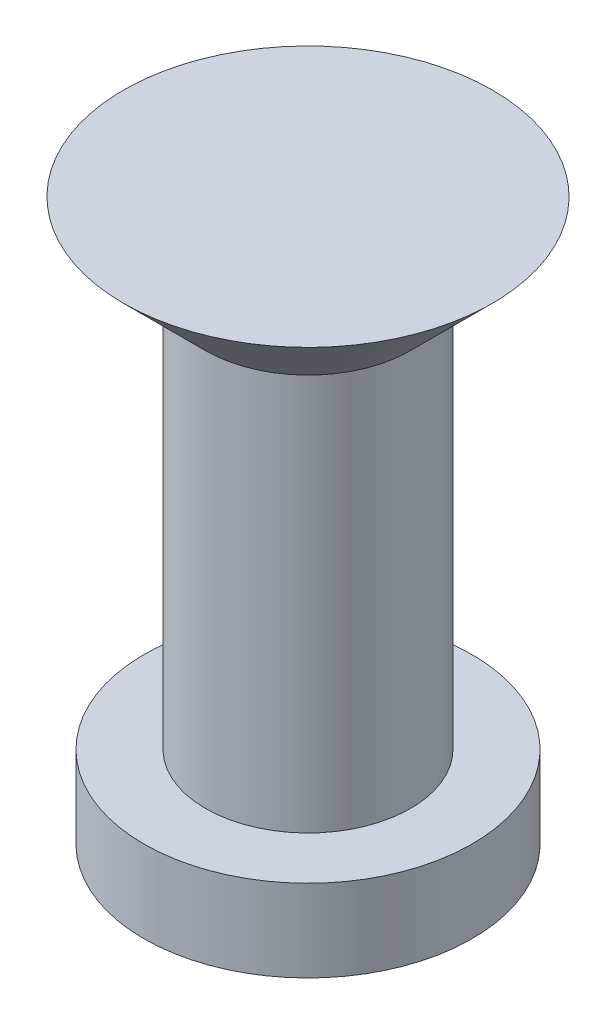
SolidWorks part; units mm, degrees
material "АМг5"
ref_plane "Спереди" through (0, 0, 0) normal (0, 0, 1) x (1, 0, 0)
ref_plane "Сверху" through (0, 0, 0) normal (0, 1, 0) x (1, 0, 0)
ref_plane "Справа" through (0, 0, 0) normal (1, 0, 0) x (0, 0, -1)
sketch "Эскиз1" plane through (0, 0, 0) normal (0, 0, 1) x (1, 0, 0)
  line L0 (0, 26.7181) -> (0, 0) construction
  line L1 (0, 8.2) -> (2.7, 8.2)
  line L2 (2.7, 8.2) -> (1.5, 7)
  line L3 (1.5, 7) -> (1.5, 1.2)
  line L4 (1.5, 1.2) -> (2.4, 1.2)
  line L5 (2.4, 1.2) -> (2.4, 0)
  line L6 (2.4, 0) -> (0, 0)
  line L7 (0, 8.2) -> (0, 0)
  dimension "D1" = 45
  dimension "D2" = 4.8
  dimension "D3" = 3
  dimension "D4" = 1.2
  dimension "D5" = 1.2
  dimension "D6" = 7
revolve "Повернуть1" add sketch "Эскиз1" angle 360 about L0
equation "\"D2@Эскиз1\"=1.6*\"D3@Эскиз1\""
equation "\"D4@Эскиз1\"=0.4*\"D3@Эскиз1\""
